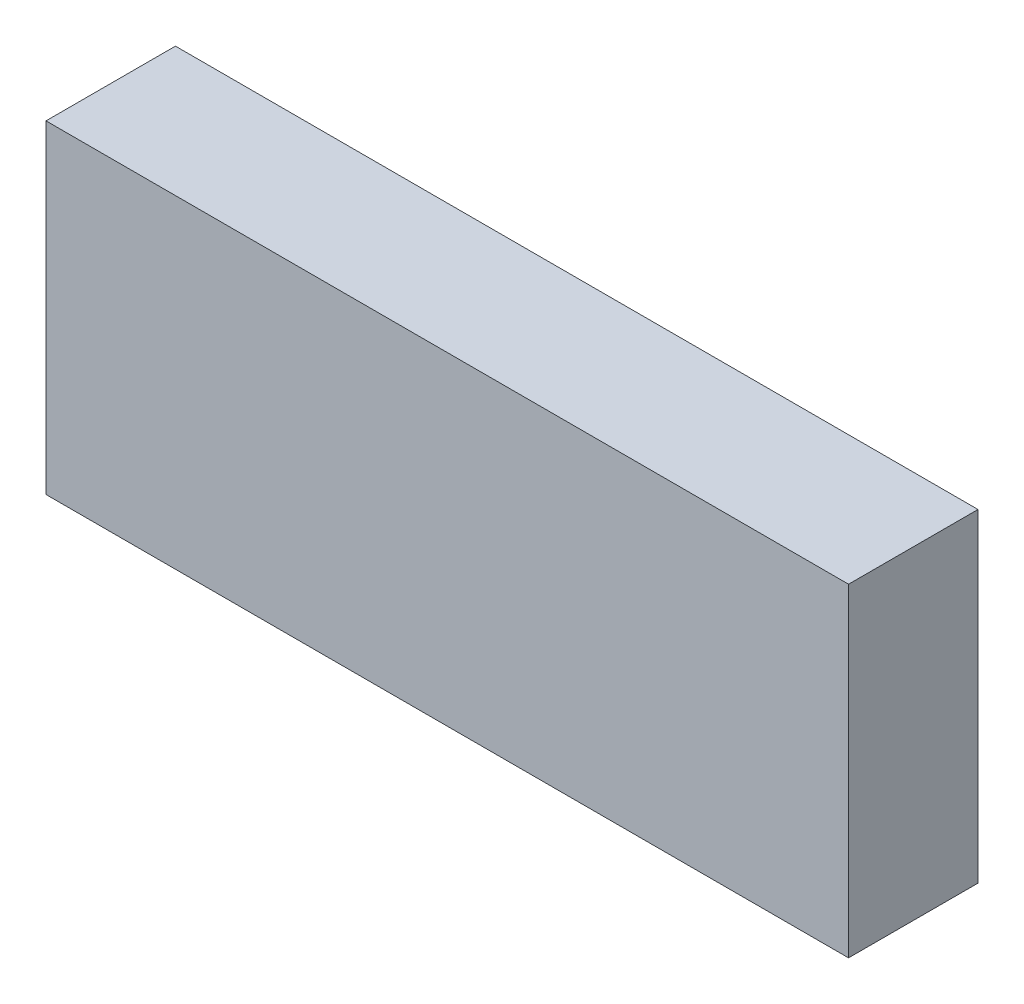
SolidWorks part; units mm, degrees
ref_plane "Přední rovina" through (0, 0, 0) normal (0, 0, 1) x (1, 0, 0)
ref_plane "Horní rovina" through (0, 0, 0) normal (0, 1, 0) x (1, 0, 0)
ref_plane "Pravá rovina" through (0, 0, 0) normal (1, 0, 0) x (0, 0, -1)
sketch "Skica1" plane through (0, 0, 0) normal (0, 0, 1) x (1, 0, 0)
  line L1 (0, 0) -> (12.4, 0)
  line L2 (0, 0) -> (0, 5)
  line L3 (0, 5) -> (12.4, 5)
  line L4 (12.4, 0) -> (12.4, 5)
  dimension "D1" = 5
  dimension "D2" = 12.4
extrude "Přidat vysunutím1" add sketch "Skica1" along normal blind 2
